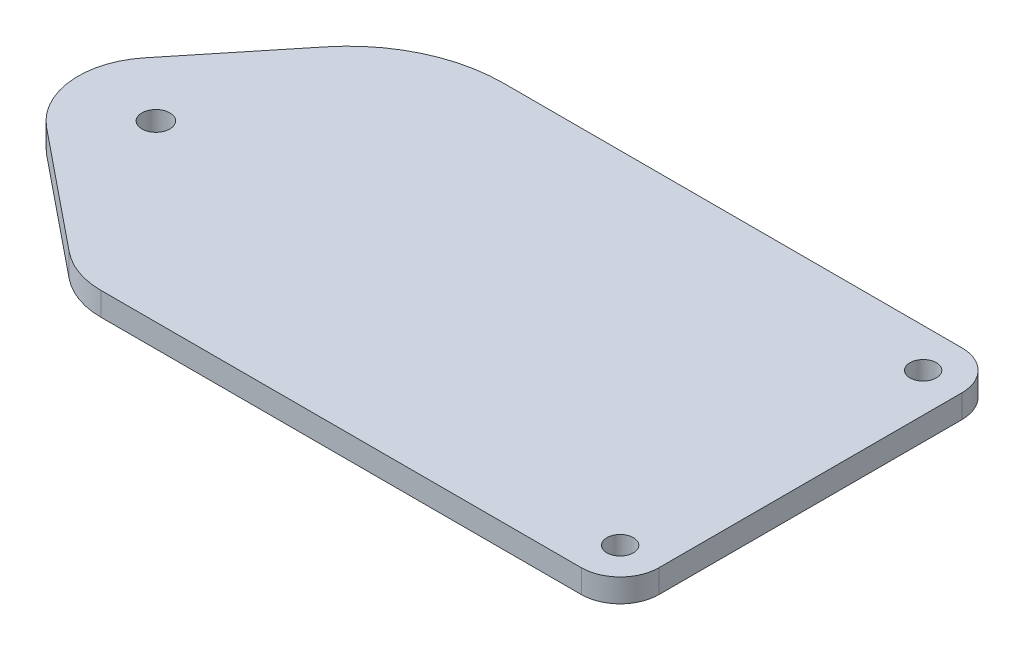
SolidWorks part; units mm, degrees
ref_plane "Front Plane" through (0, 0, 0) normal (0, 0, 1) x (1, 0, 0)
ref_plane "Top Plane" through (0, 0, 0) normal (0, 1, 0) x (1, 0, 0)
ref_plane "Right Plane" through (0, 0, 0) normal (1, 0, 0) x (0, 0, -1)
sketch "Sketch1" plane through (0, 0, 0) normal (0, 1, 0) x (1, 0, 0)
  line L4 (-39.0073, -39.0929) -> (22.8329, -39.0929)
  line L5 (-36.1435, 9.9071) -> (22.8329, 9.9071)
  line L8 (-51.6849, 2.4954) -> (-62.1123, -10.3783)
  line L9 (-45.3014, -36.8636) -> (-60.6357, -24.4432)
  line L10 (27.8329, 4.9071) -> (27.8329, -34.0929)
  arc A6 (-36.1435, 9.9071) -> (-51.6849, 2.4954) centre (-36.1435, -10.0929) ccw
  arc A7 (-62.1123, -10.3783) -> (-60.6357, -24.4432) centre (-54.3416, -16.6724) ccw
  arc A8 (-39.0073, -39.0929) -> (-45.3014, -36.8636) centre (-39.0073, -29.0929) cw
  arc A9 (27.8329, 4.9071) -> (22.8329, 9.9071) centre (22.8329, 4.9071) ccw
  arc A10 (27.8329, -34.0929) -> (22.8329, -39.0929) centre (22.8329, -34.0929) cw
  circle A12 centre (22.8329, 4.9071) radius 1.7
  circle A13 centre (22.8329, -34.0929) radius 1.7
  dimension "D1" = 5
  dimension "D2" = 5
  dimension "D4" = 10
  dimension "D5" = 10
extrude "Boss-Extrude2" add sketch "Sketch1" along normal blind 3
sketch "Sketch3" plane through (0, 0, 0) normal (0, -1, 0) x (1, 0, 0)
  line L13 (19.7833, -5.927) -> (19.7833, 35.073)
  line L14 (-41.2167, 36.073) -> (18.7833, 36.073)
  line L15 (-42.2167, -5.927) -> (-42.2167, 35.073)
  line L16 (-41.2167, -6.927) -> (18.7833, -6.927)
  line L17 (-64.3365, 16.992) -> (-64.3854, 16.992)
  arc A14 (19.7833, 35.073) -> (18.7833, 36.073) centre (18.7833, 35.073) ccw
  arc A15 (19.7833, -5.927) -> (18.7833, -6.927) centre (18.7833, -5.927) cw
  arc A16 (-41.2167, 36.073) -> (-42.2167, 35.073) centre (-41.2167, 35.073) ccw
  arc A17 (-41.2167, -6.927) -> (-42.2167, -5.927) centre (-41.2167, -5.927) cw
  arc A18 (-60.6357, 24.4432) -> (-62.1123, 10.3783) centre (-54.3416, 16.6724) ccw construction
extrude "Boss-Extrude3" add sketch "Sketch3" along normal blind 3 contours A17 L16 A15 L13 A14 L14 A16 L15
sketch "Sketch4" plane through (0, 3, 0) normal (0, 1, 0) x (1, 0, 0)
  circle A0 centre (-54.3416, -16.6724) radius 1.8
extrude "Cut-Extrude1" cut sketch "Sketch4" against normal blind 5
